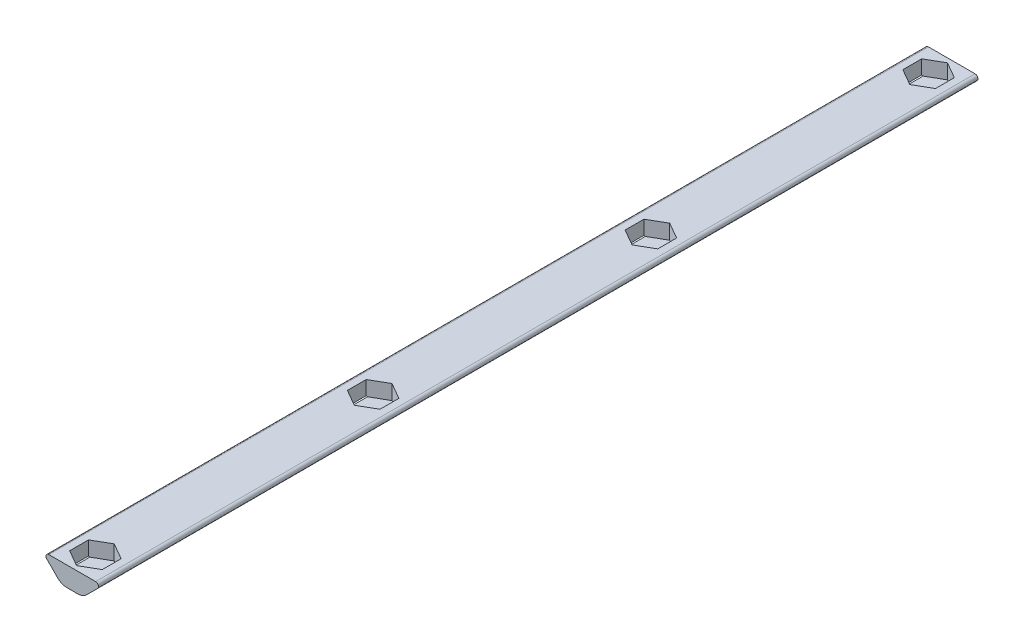
SolidWorks part; units mm, degrees
ref_plane "Front Plane" through (0, 0, 0) normal (0, 0, 1) x (1, 0, 0)
ref_plane "Top Plane" through (0, 0, 0) normal (0, 1, 0) x (1, 0, 0)
ref_plane "Right Plane" through (0, 0, 0) normal (1, 0, 0) x (0, 0, -1)
sketch "Sketch1" plane through (0, 0, 0) normal (0, 0, 1) x (-1, 0, 0)
  line L0 (-1.1346, 4.5379) -> (1.1346, 4.5379) construction
  line L1 (-3.2559, 3.6592) -> (-5.5957, 1.3194) construction
  line L2 (-5.0491, 0) -> (5.0491, 0) construction
  line L3 (3.2559, 3.6592) -> (5.5957, 1.3194) construction
  line L4 (-1.1346, 4.3879) -> (1.1346, 4.3879)
  line L5 (3.1498, 3.5532) -> (5.4896, 1.2134)
  line L6 (-5.0491, 0.15) -> (5.0491, 0.15)
  line L7 (-3.1498, 3.5532) -> (-5.4896, 1.2134)
  arc A0 (-1.1346, 4.5379) -> (-3.2559, 3.6592) centre (-1.1346, 1.5379) ccw construction
  arc A1 (-5.5957, 1.3194) -> (-5.0491, 0) centre (-5.0491, 0.7729) ccw construction
  arc A2 (5.0491, 0) -> (5.5957, 1.3194) centre (5.0491, 0.7729) ccw construction
  arc A3 (1.1346, 4.5379) -> (3.2559, 3.6592) centre (1.1346, 1.5379) cw construction
  arc A4 (1.1346, 4.3879) -> (3.1498, 3.5532) centre (1.1346, 1.5379) cw
  arc A5 (5.0491, 0.15) -> (5.4896, 1.2134) centre (5.0491, 0.7729) ccw
  arc A6 (-5.4896, 1.2134) -> (-5.0491, 0.15) centre (-5.0491, 0.7729) ccw
  arc A7 (-1.1346, 4.3879) -> (-3.1498, 3.5532) centre (-1.1346, 1.5379) ccw
  point P2 (0, 0)
  dimension "D2" = 3
  dimension "D4" = 0.7729
  dimension "D7" = 0.7729
  dimension "D8" = 3
  dimension "D9" = 1.4282
  dimension "D1" = 2.2691
  dimension "D3" = 3.3089
  dimension "D5" = 10.0983
  dimension "D6" = 3.3089
  dimension "D10" = 0.15
extrude "Boss-Extrude1" add sketch "Sketch1" along normal blind 190
sketch "Sketch2" plane through (0, -0.15, 0) normal (0, 1, 0) x (1, 0, 0)
  line L0 (5.0491, -190) -> (5.0491, 0) construction
  line L1 (0, -0.9297) -> (-3.525, -2.9648)
  line L2 (-3.525, -2.9648) -> (-3.525, -7.0352)
  line L3 (-3.525, -7.0352) -> (0, -9.0703)
  line L4 (0, -9.0703) -> (3.525, -7.0352)
  line L5 (3.525, -7.0352) -> (3.525, -2.9648)
  line L6 (3.525, -2.9648) -> (0, -0.9297)
  line L7 (0, -60.9297) -> (-3.525, -62.9648)
  line L8 (-3.525, -62.9648) -> (-3.525, -67.0352)
  line L9 (-3.525, -67.0352) -> (0, -69.0703)
  line L10 (0, -69.0703) -> (3.525, -67.0352)
  line L11 (3.525, -67.0352) -> (3.525, -62.9648)
  line L12 (3.525, -62.9648) -> (0, -60.9297)
  line L13 (0, -120.9297) -> (-3.525, -122.9648)
  line L14 (-3.525, -122.9648) -> (-3.525, -127.0352)
  line L15 (-3.525, -127.0352) -> (0, -129.0703)
  line L16 (0, -129.0703) -> (3.525, -127.0352)
  line L17 (3.525, -127.0352) -> (3.525, -122.9648)
  line L18 (3.525, -122.9648) -> (0, -120.9297)
  line L19 (0, -180.9297) -> (-3.525, -182.9648)
  line L20 (-3.525, -182.9648) -> (-3.525, -187.0352)
  line L21 (-3.525, -187.0352) -> (0, -189.0703)
  line L22 (0, -189.0703) -> (3.525, -187.0352)
  line L23 (3.525, -187.0352) -> (3.525, -182.9648)
  line L24 (3.525, -182.9648) -> (0, -180.9297)
  circle A0 centre (0, -5) radius 3.525 construction
  dimension "D1" = 7.05
  dimension "D2" = 5
  dimension "D4" = 60
  dimension "D3" = 4
extrude "Cut-Extrude1" cut sketch "Sketch2" against normal blind 3.2
